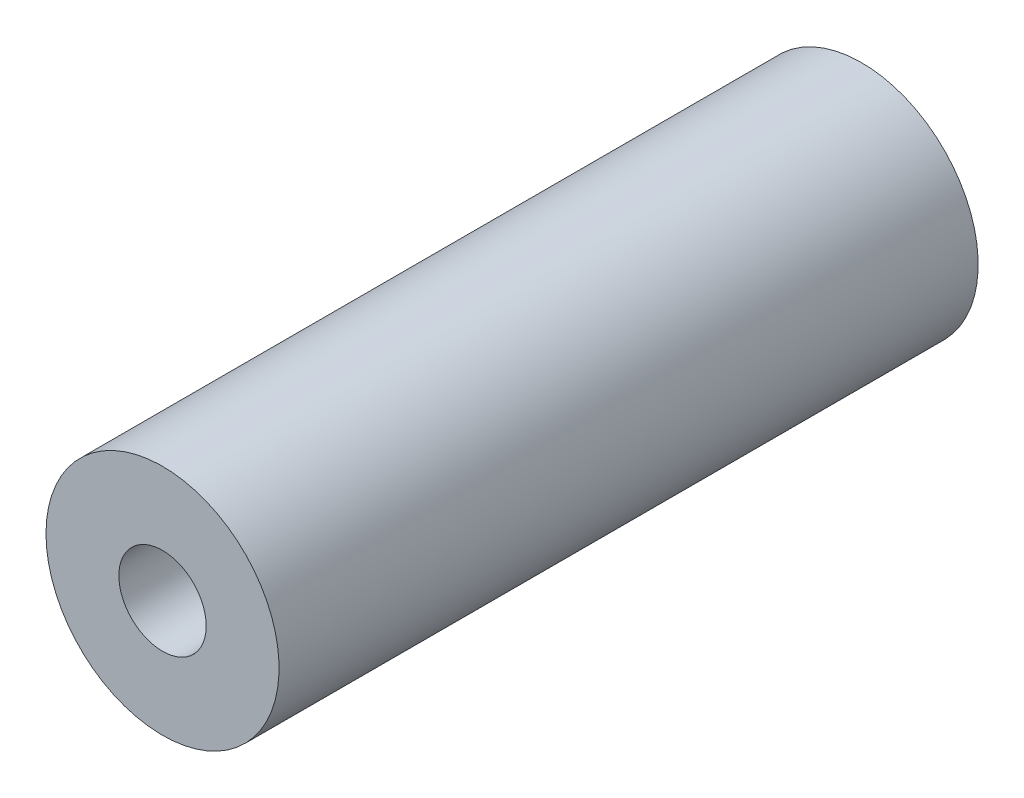
SolidWorks part; units mm, degrees
ref_plane "Front Plane" through (0, 0, 0) normal (0, 0, 1) x (1, 0, 0)
ref_plane "Top Plane" through (0, 0, 0) normal (0, 1, 0) x (1, 0, 0)
ref_plane "Right Plane" through (0, 0, 0) normal (1, 0, 0) x (0, 0, -1)
sketch "Sketch1" plane through (0, 0, 0) normal (0, 0, 1) x (1, 0, 0)
  circle A0 centre (0, 0) radius 3.175
  dimension "D1" = 6.35
extrude "Boss-Extrude1" add sketch "Sketch1" along normal blind 19.05
sketch "Sketch2" plane through (0, 0, 19.05) normal (0, 0, 1) x (1, 0, 0)
  circle A0 centre (0, 0) radius 1.1906
  dimension "D1" = 2.3813
extrude "Cut-Extrude1" cut sketch "Sketch2" against normal offset from surface (6.35 mm away) 6.35 up to face at (3.175, 0, 19.05)
